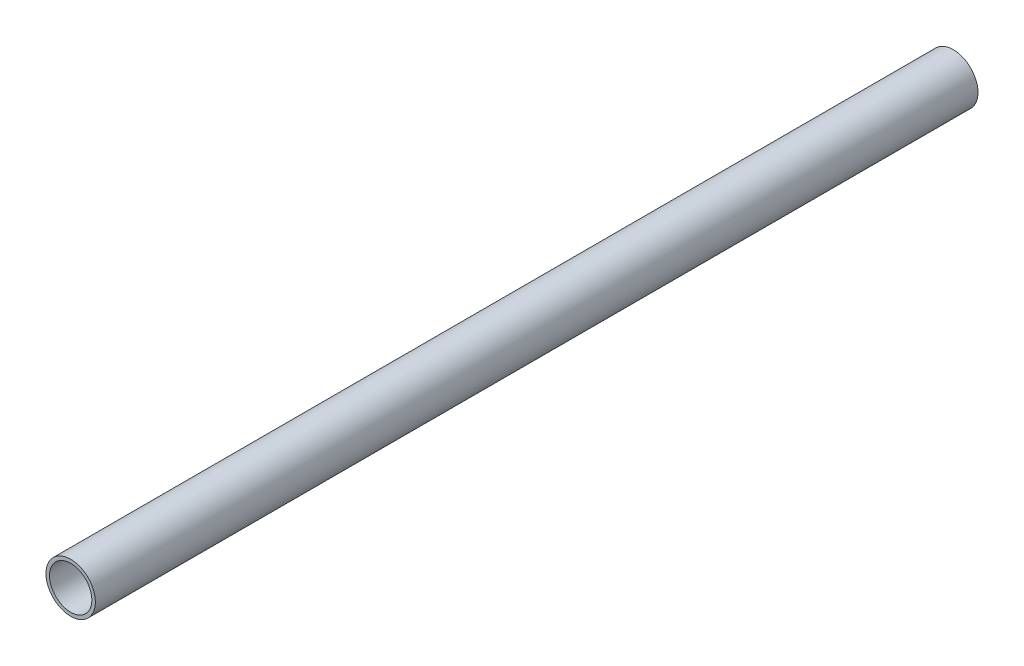
SolidWorks part; units mm, degrees
material "EM-CF"
ref_plane "Płaszczyzna przednia" through (0, 0, 0) normal (0, 0, 1) x (1, 0, 0)
ref_plane "Płaszczyzna górna" through (0, 0, 0) normal (0, 1, 0) x (1, 0, 0)
ref_plane "Płaszczyzna prawa" through (0, 0, 0) normal (1, 0, 0) x (0, 0, -1)
sketch "Szkic1" plane through (0, 0, 0) normal (0, 0, 1) x (1, 0, 0)
  circle A0 centre (0, 0) radius 6
  circle A1 centre (0, 0) radius 7
  dimension "D1" = 1
  dimension "D2" = 14
extrude "Dodanie-wyciągnięcie1" add sketch "Szkic1" along normal blind 250
